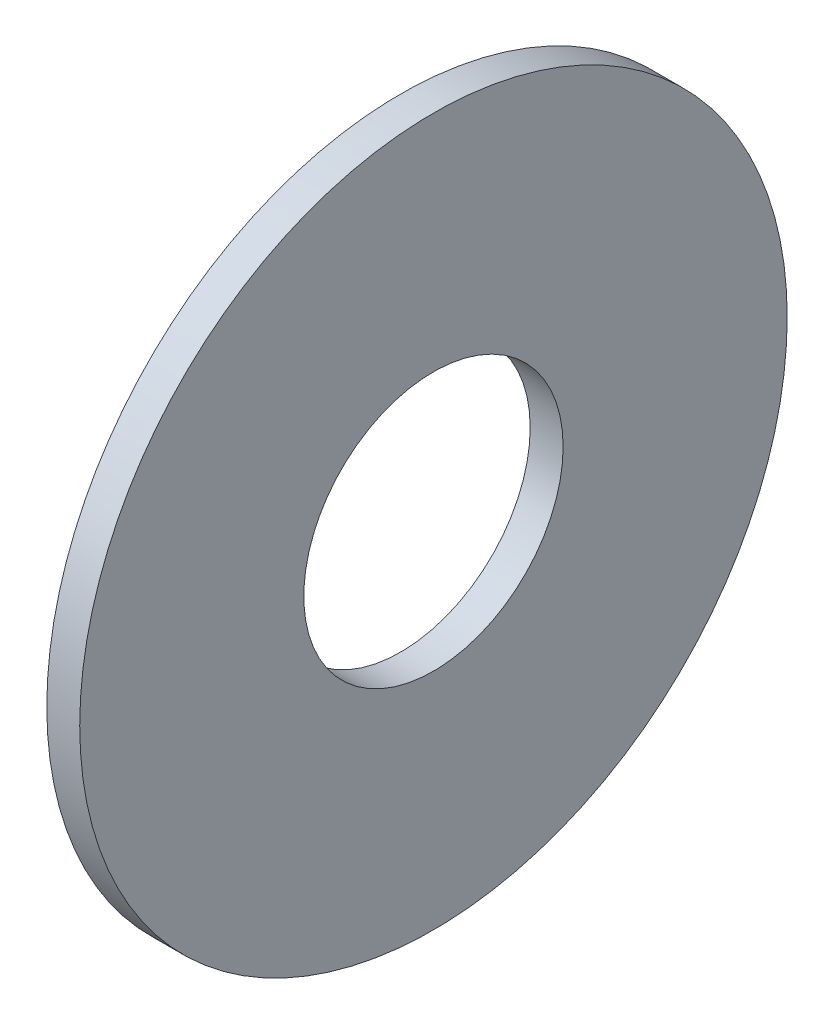
SolidWorks part; units mm, degrees
ref_plane "Front Plane" through (0, 0, 0) normal (0, 0, 1) x (1, 0, 0)
ref_plane "Top Plane" through (0, 0, 0) normal (0, 1, 0) x (1, 0, 0)
ref_plane "Right Plane" through (0, 0, 0) normal (1, 0, 0) x (0, 0, -1)
sketch "Sketch1" plane through (0, 0, 0) normal (1, 0, 0) x (0, 0, -1)
  circle A0 centre (0, 0) radius 8.7312
  circle A1 centre (0, 0) radius 3.2004
  dimension "OD" = 17.4625
  dimension "Shaft Dia" = 6.4008
extrude "Extrude1" add sketch "Sketch1" along normal blind 0.8128
